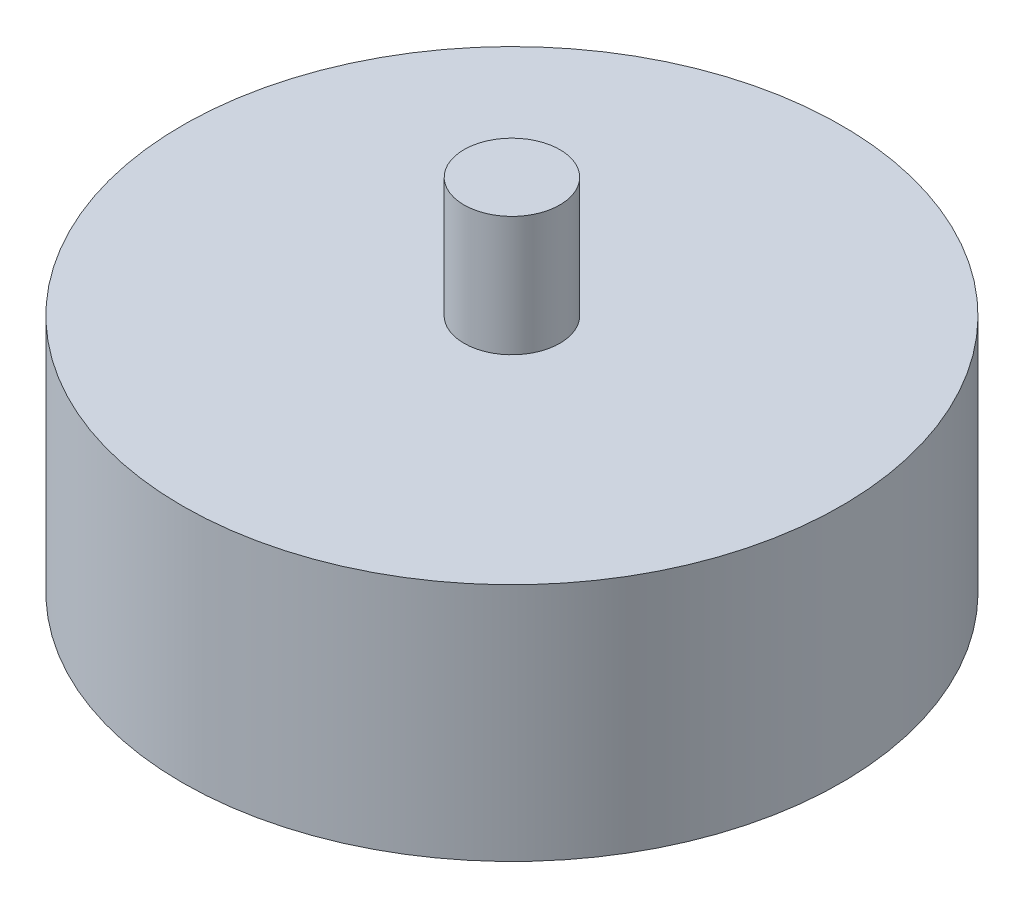
SolidWorks part; units mm, degrees
material "灰铸铁"
ref_plane "前视基准面" through (0, 0, 0) normal (0, 0, 1) x (1, 0, 0)
ref_plane "上视基准面" through (0, 0, 0) normal (0, 1, 0) x (1, 0, 0)
ref_plane "右视基准面" through (0, 0, 0) normal (1, 0, 0) x (0, 0, -1)
other "Configuration Table"
sketch "草图1" plane through (0, 0, 0) normal (0, 1, 0) x (1, 0, 0)
  circle A0 centre (0, 0) radius 27.5
  dimension "D1" = 55
extrude "凸台-拉伸1" add sketch "草图1" along normal blind 20
sketch "草图2" plane through (0, 20, 0) normal (0, 1, 0) x (1, 0, 0)
  circle A0 centre (0, 0) radius 4
  dimension "D1" = 8
extrude "凸台-拉伸2" add sketch "草图2" along normal blind 10
